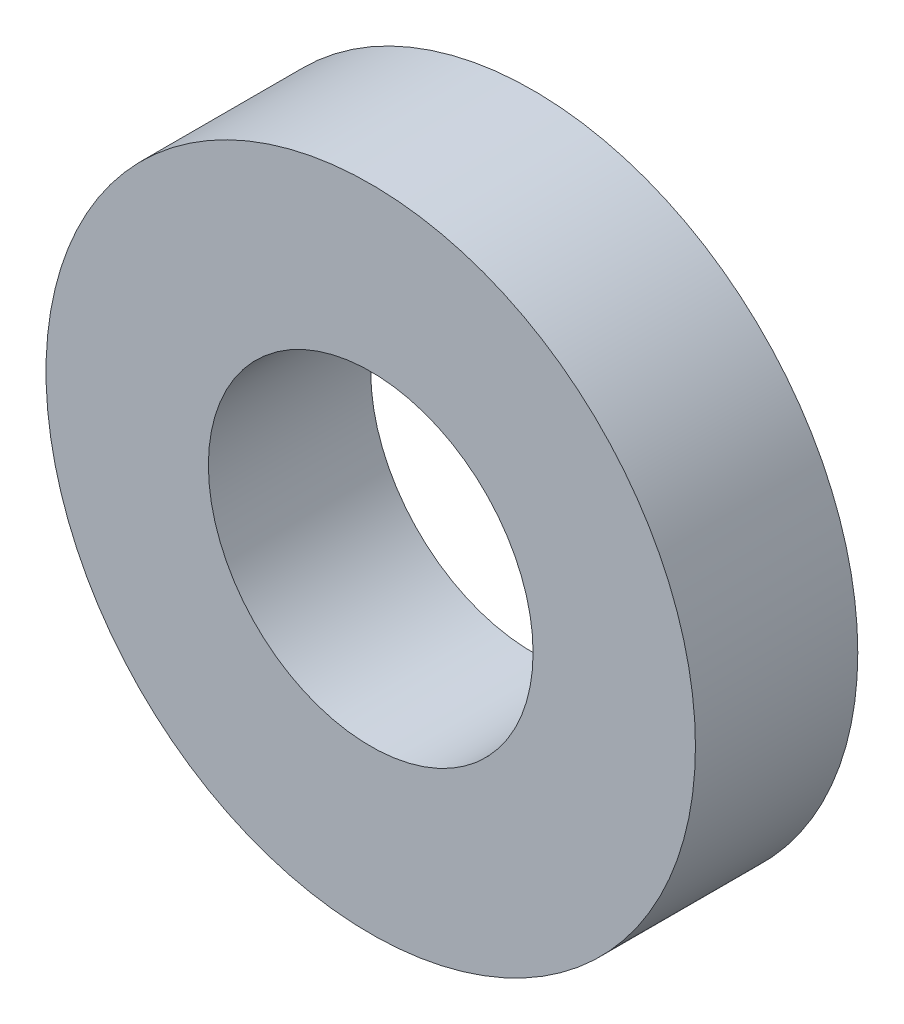
SolidWorks part; units mm, degrees
ref_plane "Front Plane" through (0, 0, 0) normal (0, 0, 1) x (1, 0, 0)
ref_plane "Top Plane" through (0, 0, 0) normal (0, 1, 0) x (1, 0, 0)
ref_plane "Right Plane" through (0, 0, 0) normal (1, 0, 0) x (0, 0, -1)
sketch "Sketch1" plane through (0, 0, 0) normal (0, 0, 1) x (1, 0, 0)
  circle A0 centre (8, 8) radius 8
  circle A1 centre (8, 8) radius 4
  dimension "D1" = 8
  dimension "D2" = 16
extrude "Profile" add sketch "Sketch1" along normal blind 4
equation "\"Profile_Depth\"= 4mm"
equation "\"D1@Profile\" = \"Profile_Depth\""
equation "\"Profile_Sketch_1\"= 8mm"
equation "\"D1@Sketch1\" = \"Profile_Sketch_1\""
equation "\"Profile_Sketch_2\"= 16mm"
equation "\"D2@Sketch1\" = \"Profile_Sketch_2\""
equation "\"EnvelopeWidth\"= 16mm"
equation "\"EnvelopeHeight\"= 16mm"
